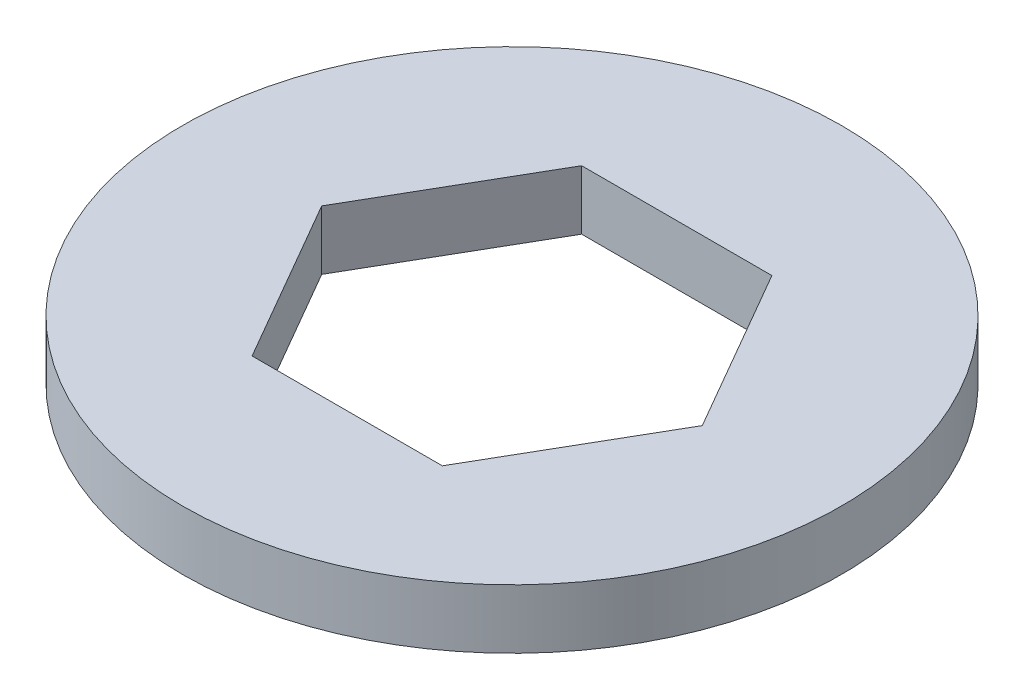
SolidWorks part; units mm, degrees
ref_plane "Front Plane" through (0, 0, 0) normal (0, 0, 1) x (1, 0, 0)
ref_plane "Top Plane" through (0, 0, 0) normal (0, 1, 0) x (1, 0, 0)
ref_plane "Right Plane" through (0, 0, 0) normal (1, 0, 0) x (0, 0, -1)
sketch "Sketch1" plane through (0, 0, 0) normal (0, 1, 0) x (1, 0, 0)
  line L1 (3.6662, 6.35) -> (-3.6662, 6.35)
  line L2 (-3.6662, 6.35) -> (-7.3323, 0)
  line L3 (-7.3323, 0) -> (-3.6662, -6.35)
  line L4 (-3.6662, -6.35) -> (3.6662, -6.35)
  line L5 (3.6662, -6.35) -> (7.3323, 0)
  line L6 (7.3323, 0) -> (3.6662, 6.35)
  circle A0 centre (0, 0) radius 6.35 construction
  circle A1 centre (0, 0) radius 12.7
  dimension "D1" = 12.7
  dimension "D2" = 25.4
extrude "Boss-Extrude1" add sketch "Sketch1" along normal mid plane 2.286
